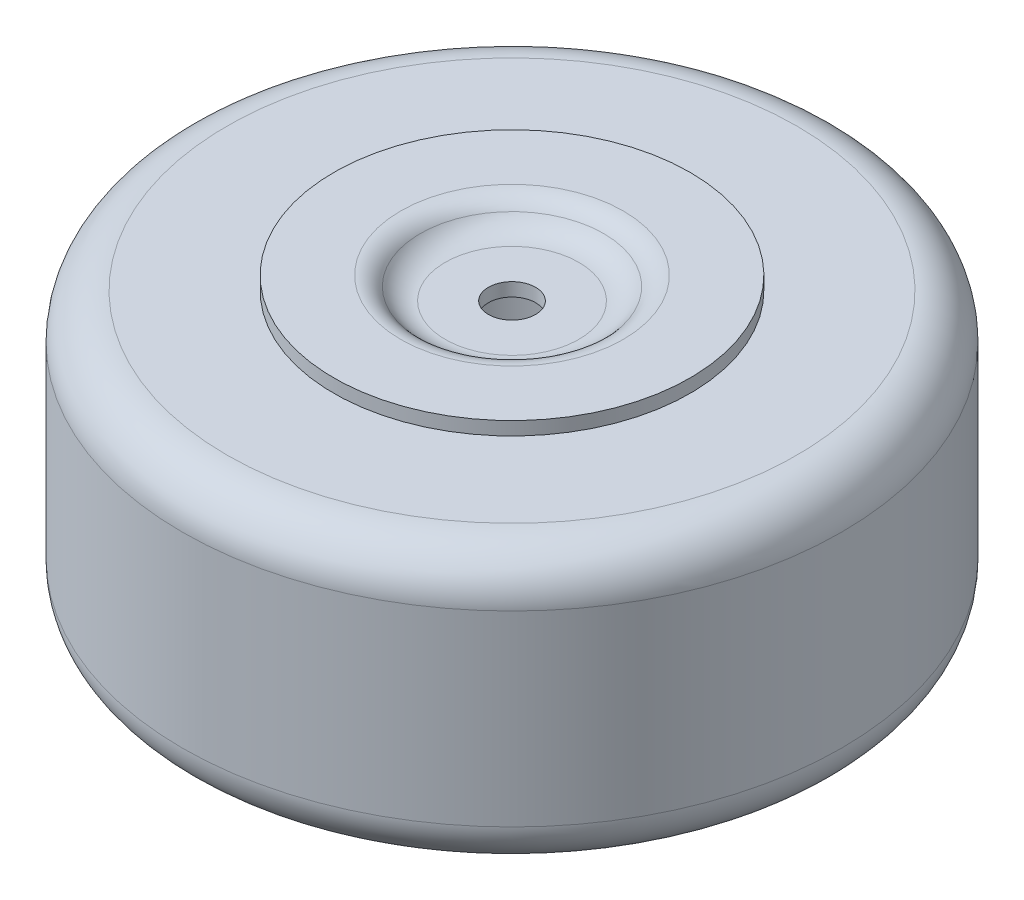
SolidWorks part; units mm, degrees
ref_plane "Front Plane" through (0, 0, 0) normal (0, 0, 1) x (1, 0, 0)
ref_plane "Top Plane" through (0, 0, 0) normal (0, 1, 0) x (1, 0, 0)
ref_plane "Right Plane" through (0, 0, 0) normal (1, 0, 0) x (0, 0, -1)
sketch "Sketch1" plane through (0, 0, 0) normal (1, 0, 0) x (0, 0, -1)
  line L0 (0, 0) -> (0, 31) construction
  line L1 (-2.65, 20.5) -> (-2.65, 10.5)
  line L2 (-2.65, 10.5) -> (-9.5, 10.5)
  line L3 (-9.5, 10.5) -> (-9.5, 5)
  line L4 (-14.5, 0) -> (-32, 0)
  line L5 (-37, 5) -> (-37, 26)
  line L6 (-32, 31) -> (-14.5, 31)
  line L7 (-9.5, 26) -> (-9.5, 20.5)
  line L8 (-9.5, 20.5) -> (-2.65, 20.5)
  line L9 (-2.65, 15.5) -> (-37, 15.5) construction
  arc A0 (-9.5, 5) -> (-14.5, 0) centre (-14.5, 5) cw
  arc A1 (-32, 0) -> (-37, 5) centre (-32, 5) cw
  arc A2 (-37, 26) -> (-32, 31) centre (-32, 26) cw
  arc A3 (-14.5, 31) -> (-9.5, 26) centre (-14.5, 26) cw
  dimension "D6" = 5
  dimension "D7" = 5
  dimension "D1" = 31
  dimension "D2" = 74
  dimension "D3" = 19
  dimension "D4" = 5.3
  dimension "D5" = 10
revolve "Revolve1" add sketch "Sketch1" angle 360 about L0
sketch "Sketch2" plane through (0, 0, 0) normal (1, 0, 0) x (0, 0, -1)
  line L0 (0, 0) -> (0, 48.821) construction
  line L1 (-20, 31) -> (-12.5, 31)
  line L3 (-7.5, 28.5) -> (0, 28.5)
  line L4 (0, 28.5) -> (0, 30)
  line L6 (-20, 31) -> (-20, 32.5)
  line L7 (-20, 32.5) -> (-12.5, 32.5)
  line L8 (-7.5, 30) -> (0, 30)
  line L9 (32, 31) -> (-32, 31) construction
  line L14 (-18.5, 32.5) -> (-12.5, 32.5) construction
  line L15 (-7.5, 30) -> (-1.5, 30) construction
  line L16 (-1.5, 30) -> (-1.5, 30) construction
  line L17 (-18.5, 32.5) -> (-18.5, 32.5) construction
  arc A0 (-12.5, 31) -> (-11.5, 30.5) centre (-12.5, 29.75) cw
  arc A1 (-11.5, 30.5) -> (-7.5, 28.5) centre (-7.5, 33.5) ccw
  arc A2 (-12.5, 32.5) -> (-10.3, 31.4) centre (-12.5, 29.75) cw
  arc A3 (-10.3, 31.4) -> (-7.5, 30) centre (-7.5, 33.5) ccw
  dimension "D5" = 5
  dimension "D1" = 40
  dimension "D2" = 25
  dimension "D3" = 15
  dimension "D4" = 1.5
  dimension "D6" = 1
revolve "Revolve2" add sketch "Sketch2" angle 360 about L0
sketch "Sketch3" plane through (0, 28.5, 0) normal (0, -1, 0) x (1, 0, 0)
  circle A0 centre (0, 0) radius 2.65 construction
  circle A1 centre (0, 0) radius 2.65
extrude "Cut-Extrude1" cut sketch "Sketch3" against normal through all
